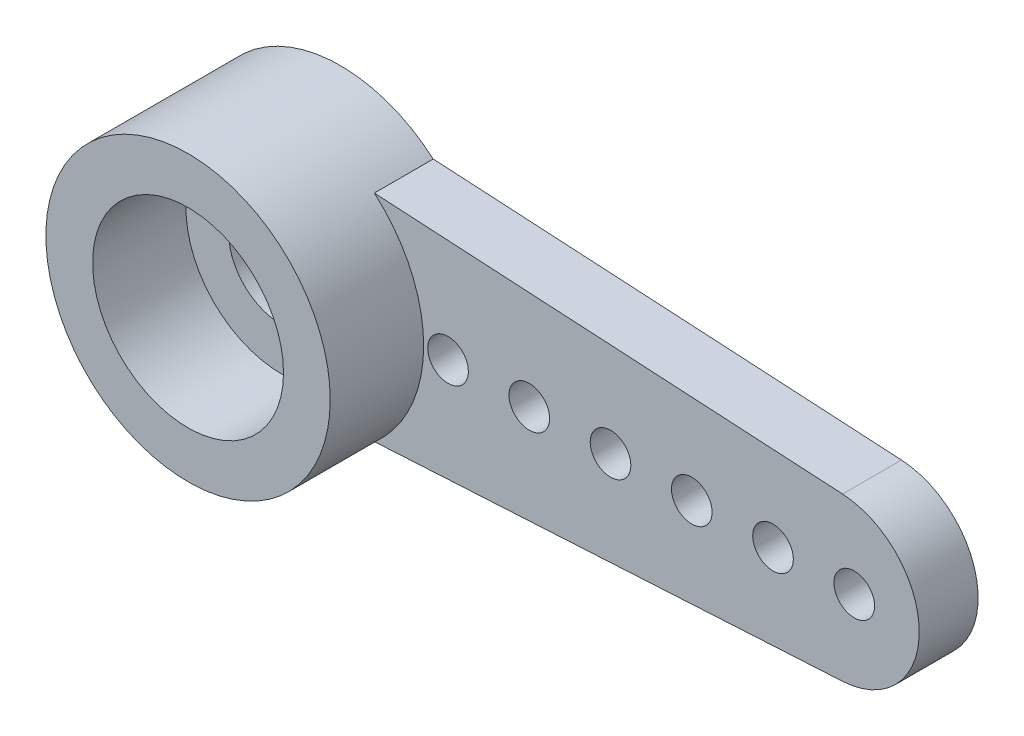
SolidWorks part; units mm, degrees
material "ABS"
ref_plane "前视基准面" through (0, 0, 0) normal (0, 0, 1) x (1, 0, 0)
ref_plane "上视基准面" through (0, 0, 0) normal (0, 1, 0) x (1, 0, 0)
ref_plane "右视基准面" through (0, 0, 0) normal (1, 0, 0) x (0, 0, -1)
other "Configuration Table"
sketch "草图1" plane through (0, 0, 0) normal (0, 0, 1) x (1, 0, 0)
  line L0 (-4.9058, 3.0576) -> (16.7875, 1.8282)
  line L1 (-3.5, 8.2939) -> (-3.5, -8.5966) construction
  line L2 (16.004, -1.8726) -> (-5.7967, -3.1081)
  line L3 (15.7, 7.2301) -> (15.7, -7.2734) construction
  line L4 (2.2864, 6.2453) -> (2.2864, -4.4515) construction
  circle A0 centre (13.7, 0) radius 2
  circle A1 centre (0, 0) radius 2.7751
  circle A2 centre (0, 0) radius 3.5
  point P14 (2.2864, -2.65)
  point P15 (2.2864, 2.65)
  dimension "D2" = 7
  dimension "D3" = 4
  dimension "D1" = 19.2
  dimension "D4" = 5.3
extrude "凸台-拉伸1" add sketch "草图1" along normal blind 1.45 contours L2 A2 L0 A1 | A1 | L0 A2 L2 A1 | L0 A2 | L2 A2 | A2 L2 A0 L0 | A0 A2
sketch "草图2" plane through (0, 0, 1.45) normal (0, 0, 1) x (1, 0, 0)
  circle A1 centre (0, 0) radius 2.35
  circle A2 centre (0, 0) radius 3.5
  arc A3 (2.2864, 2.65) -> (2.2864, -2.65) centre (0, 0) ccw construction
  dimension "D1" = 4.7
extrude "凸台-拉伸2" add sketch "草图2" along normal blind 2.3
sketch "草图3" plane through (0, 0, 0) normal (0, 0, -1) x (-1, 0, 0)
  circle A0 centre (0, 0) radius 2.3
  dimension "D1" = 4.6
extrude "切除-拉伸1" cut sketch "草图3" against normal blind 0.7
sketch "草图4" plane through (0, 0, 0.7) normal (0, 0, -1) x (-1, 0, 0)
  circle A0 centre (0, 0) radius 1.3
  dimension "D1" = 2.6
extrude "切除-拉伸2" cut sketch "草图4" against normal through all
sketch "草图5" plane through (0, 0, 0) normal (0, 0, -1) x (-1, 0, 0)
  line L0 (-15.7, 4.7285) -> (-15.7, -4.2754) construction
  line L1 (-14.6, 4.1484) -> (-14.6, -4.5312) construction
  arc A1 (-13.8132, 1.9968) -> (-13.8132, -1.9968) centre (-13.7, 0) ccw construction
  circle A2 centre (-14.1, 0) radius 0.5
  dimension "D1" = 1
  dimension "D2" = 1.1
extrude "切除-拉伸3" cut sketch "草图5" against normal through all contours A2
pattern_linear "阵列(线性)1" count 6 spacing 2 along (-1, 0, 0) of "切除-拉伸3"
